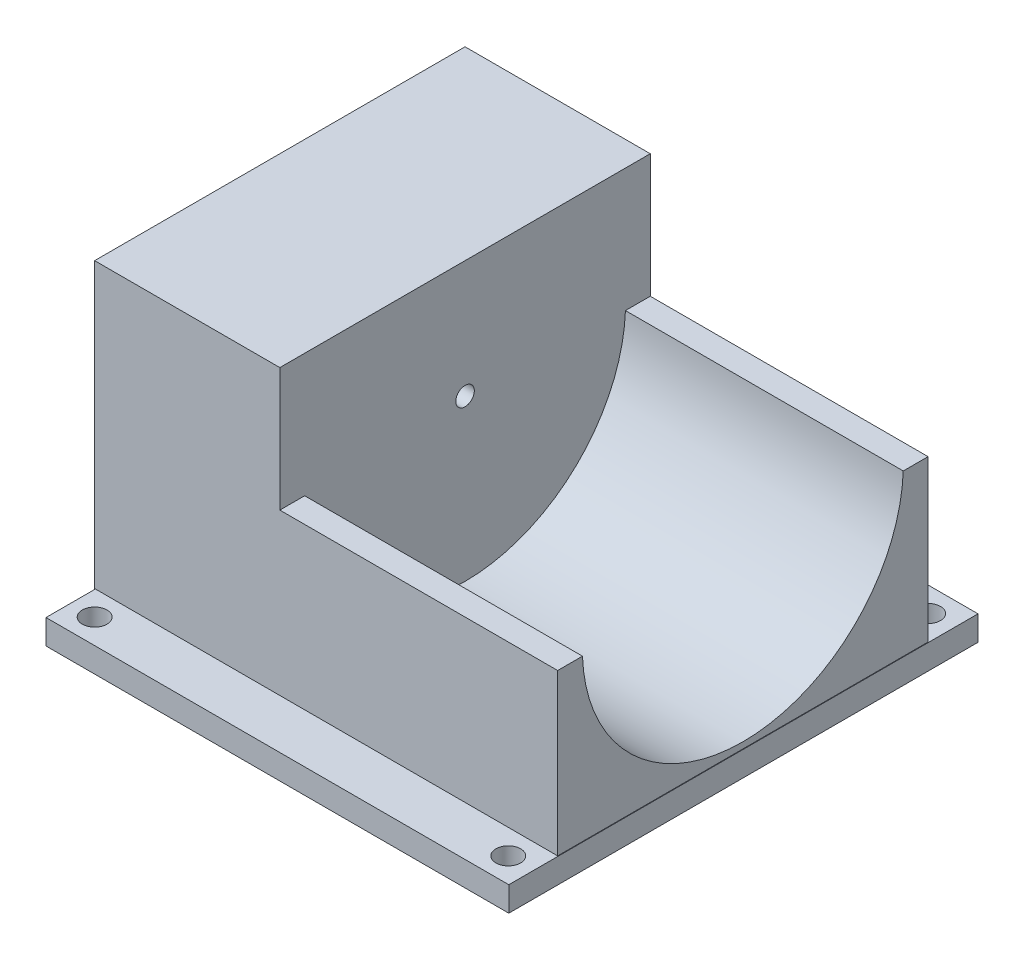
SolidWorks part; units mm, degrees
ref_plane "Front Plane" through (0, 0, 0) normal (0, 0, 1) x (1, 0, 0)
ref_plane "Top Plane" through (0, 0, 0) normal (0, 1, 0) x (1, 0, 0)
ref_plane "Right Plane" through (0, 0, 0) normal (1, 0, 0) x (0, 0, -1)
sketch "Sketch1" plane through (0, 0, 0) normal (0, 1, 0) x (1, 0, 0)
  line L1 (15, -30) -> (-15, -30)
  line L2 (15, -30) -> (15, 30)
  line L3 (15, 30) -> (-15, 30)
  line L4 (-15, -30) -> (-15, 30)
  line L5 (15, -30) -> (-15, 30) construction
  line L6 (15, 30) -> (-15, -30) construction
  point P0 (0, 0)
  dimension "D1" = 30
  dimension "D2" = 60
extrude "Boss-Extrude1" add sketch "Sketch1" along normal blind 50
sketch "Sketch2" plane through (15, 0, 0) normal (1, 0, 0) x (0, 0, -1)
  line L0 (-25.981, 30.0068) -> (-30, 30.0068)
  line L1 (-30, 50) -> (-30, 0) construction
  line L2 (-30, 30.0068) -> (-30, 0)
  line L3 (-30, 0) -> (30, 0)
  line L4 (30, 0) -> (30, 30.0068)
  line L5 (30, 50) -> (30, 0) construction
  line L6 (30, 30.0068) -> (25.981, 30.0068)
  arc A0 (-25.981, 30.0068) -> (25.981, 30.0068) centre (0, 31) ccw
  point P14 (0, 5)
  dimension "D1" = 26
  dimension "D2" = 5
extrude "Boss-Extrude2" add sketch "Sketch2" along normal blind 45
sketch "Sketch3" plane through (0, 0, 0) normal (0, -1, 0) x (1, 0, 0)
  line L0 (-15, 30) -> (60, 30) construction
  line L3 (-15, -30) -> (-15, 30) construction
  line L4 (60, 30) -> (60, -30) construction
  line L5 (60, -30) -> (-15, -30) construction
  line L7 (-14.8775, 38) -> (60.0862, 38)
  line L8 (-14.8775, 38) -> (-14.8775, -38)
  line L9 (-14.8775, -38) -> (60.0862, -38)
  line L10 (60.0862, 38) -> (60.0862, -38)
  circle A0 centre (-11, 34) radius 2
  circle A1 centre (56, 34) radius 2
  circle A2 centre (56, -34) radius 2
  circle A3 centre (-11, -34) radius 2
  dimension "D1" = 4
  dimension "D2" = 4
  dimension "D3" = 4
  dimension "D4" = 4
  dimension "D5" = 4
  dimension "D6" = 4
  dimension "D7" = 4
extrude "Boss-Extrude3" add sketch "Sketch3" against normal blind 4
sketch "Sketch4" plane through (15, 0, 0) normal (1, 0, 0) x (0, 0, -1)
  circle A0 centre (0, 31) radius 1.5
  point P3 (0, 0)
  dimension "D1" = 3
extrude "Cut-Extrude1" cut sketch "Sketch4" against normal blind 5
